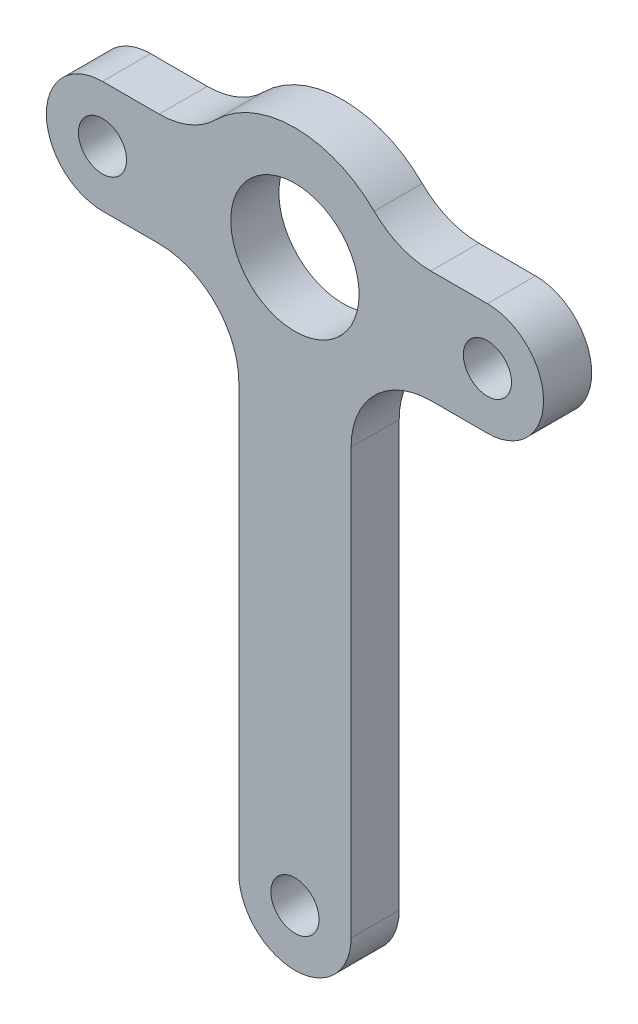
SolidWorks part; units mm, degrees
ref_plane "前视基准面" through (0, 0, 0) normal (0, 0, 1) x (1, 0, 0)
ref_plane "上视基准面" through (0, 0, 0) normal (0, 1, 0) x (1, 0, 0)
ref_plane "右视基准面" through (0, 0, 0) normal (1, 0, 0) x (0, 0, -1)
sketch "草图1" plane through (0, 0, 0) normal (0, 0, 1) x (1, 0, 0)
  line L0 (0, 7.6751) -> (0, -52.6595) construction
  line L1 (-39.1122, 0) -> (41.5493, 0) construction
  line L3 (-12, -3.5) -> (-8.5, -3.5)
  line L4 (-3.5, -8.5) -> (-3.5, -35)
  line L5 (12, -3.5) -> (8.5, -3.5)
  line L6 (3.5, -8.5) -> (3.5, -35)
  line L7 (-12, 3.5) -> (-8.4705, 3.5)
  line L8 (12, 3.5) -> (8.4705, 3.5)
  circle A0 centre (0, 0) radius 4
  circle A1 centre (-12, 0) radius 1.5
  circle A2 centre (0, -35) radius 1.5
  circle A3 centre (12, 0) radius 1.5
  arc A4 (-3.5, -35) -> (3.5, -35) centre (0, -35) ccw
  arc A5 (12, 3.5) -> (12, -3.5) centre (12, 0) cw
  arc A6 (-12, 3.5) -> (-12, -3.5) centre (-12, 0) ccw
  arc A7 (8.5, -3.5) -> (3.5, -8.5) centre (8.5, -8.5) ccw
  arc A8 (-8.5, -3.5) -> (-3.5, -8.5) centre (-8.5, -8.5) cw
  arc A9 (-4.9411, 4.9583) -> (4.9411, 4.9583) centre (0, 0) cw
  arc A10 (8.4705, 3.5) -> (4.9411, 4.9583) centre (8.4705, 8.5) cw
  arc A11 (-4.9411, 4.9583) -> (-8.4705, 3.5) centre (-8.4705, 8.5) cw
  point P25 (3.5, -3.5)
  point P28 (-3.5, -3.5)
  point P33 (6.0622, 3.5)
  point P36 (-6.0622, 3.5)
  dimension "D1" = 8
  dimension "D2" = 12
  dimension "D3" = 35
  dimension "D4" = 5
  dimension "D7" = 3
  dimension "D5" = 7
  dimension "D8" = 7
  dimension "D9" = 5
  dimension "D6" = 7
extrude "凸台-拉伸1" add sketch "草图1" along normal blind 3
